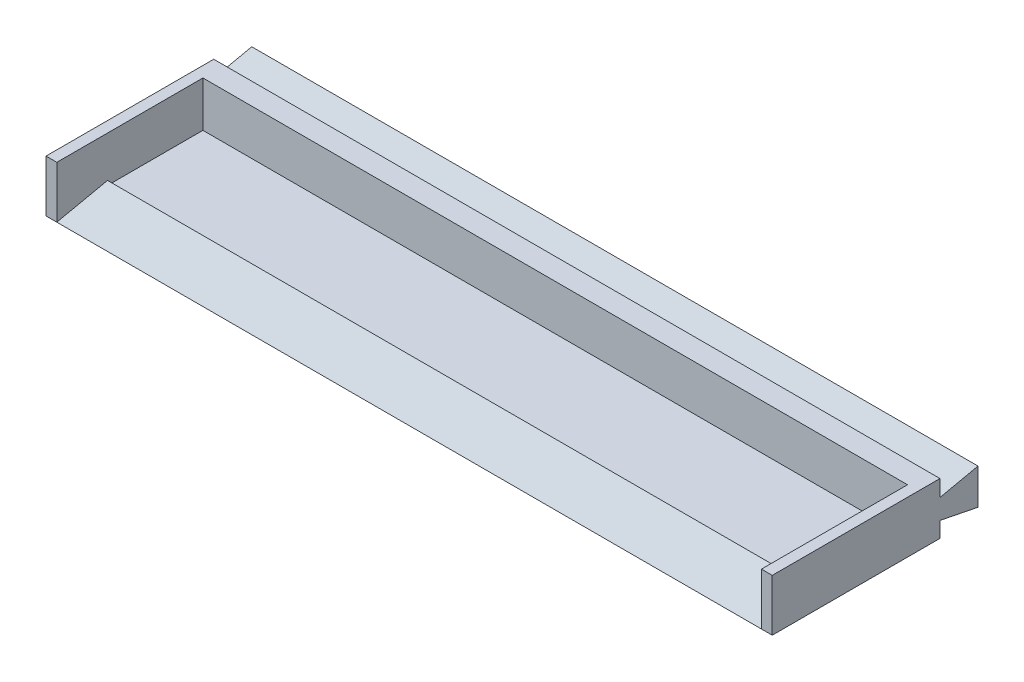
SolidWorks part; units mm, degrees
ref_plane "Front Plane" through (0, 0, 0) normal (0, 0, 1) x (1, 0, 0)
ref_plane "Top Plane" through (0, 0, 0) normal (0, 1, 0) x (1, 0, 0)
ref_plane "Right Plane" through (0, 0, 0) normal (1, 0, 0) x (0, 0, -1)
sketch "Sketch1" plane through (0, 0, 0) normal (0, 1, 0) x (1, 0, 0)
  line L1 (0, 0) -> (163, 0)
  line L2 (0, 0) -> (0, 38.8)
  line L3 (0, 38.8) -> (163, 38.8)
  line L4 (163, 0) -> (163, 38.8)
  dimension "D1" = 38.8
  dimension "D2" = 163
extrude "Boss-Extrude1" add sketch "Sketch1" along normal blind 2.5
sketch "Sketch3" plane through (163, 0, 0) normal (1, 0, 0) x (0, 0, -1)
  line L0 (0, 0) -> (11.7367, 2.5)
  line L1 (0, 2.5) -> (38.8, 2.5) construction
  line L2 (0, 2.5) -> (11.7367, 2.5)
  line L3 (0, 2.5) -> (0, 0)
  dimension "D1" = 12
extrude "Cut-Extrude1" cut sketch "Sketch3" against normal blind 168
sketch "Sketch4" plane through (163, 0, 0) normal (1, 0, 0) x (0, 0, -1)
  line L0 (38.8, 2.5) -> (38.8, 0) construction
  line L1 (11.7367, 2.5) -> (38.8, 2.5)
  line L2 (11.7367, 2.5) -> (11.7367, 1.5)
  line L3 (11.7367, 1.5) -> (38.8, 1.5)
  line L4 (38.8, 2.5) -> (38.8, 1.5)
  dimension "D1" = 1
extrude "Cut-Extrude2" cut sketch "Sketch4" against normal blind 168
sketch "Sketch5" plane through (0, 1.5, 0) normal (0, 1, 0) x (1, 0, 0)
  line L1 (0, 38.8) -> (163, 38.8)
  line L2 (0, 38.8) -> (0, 33.8)
  line L3 (0, 33.8) -> (163, 33.8)
  line L4 (163, 38.8) -> (163, 33.8)
  line L5 (163, 11.7367) -> (163, 38.8) construction
  dimension "D1" = 5
  dimension "D2" = 163
extrude "Boss-Extrude2" add sketch "Sketch5" along normal blind 10.5
sketch "Sketch6" plane through (0, 0, 0) normal (-1, 0, 0) x (0, 0, 1)
  line L1 (-38.8, 12) -> (0, 12)
  line L2 (-38.8, 12) -> (-38.8, 0)
  line L3 (-38.8, 0) -> (0, 0)
  line L4 (0, 12) -> (0, 0)
extrude "Boss-Extrude3" add sketch "Sketch6" along normal blind 2.5
sketch "Sketch7" plane through (163, 0, 0) normal (1, 0, 0) x (0, 0, -1)
  line L1 (0, 0) -> (38.8, 0)
  line L2 (0, 0) -> (0, 12)
  line L3 (0, 12) -> (38.8, 12)
  line L4 (38.8, 0) -> (38.8, 12)
extrude "Boss-Extrude4" add sketch "Sketch7" along normal blind 2.5
sketch "Sketch8" plane through (0, 0, -38.8) normal (0, 0, -1) x (-1, 0, 0)
  line L0 (2.5, 12) -> (2.5, 0) construction
  line L1 (-165.5, 12) -> (2.5, 12)
  line L2 (-165.5, 12) -> (-165.5, 0)
  line L3 (-165.5, 0) -> (2.5, 0)
  line L4 (2.5, 12) -> (2.5, 0)
  dimension "D1" = 12
extrude "Boss-Extrude5" add sketch "Sketch8" along normal blind 8.8
sketch "Sketch9" plane through (165.5, 0, 0) normal (1, 0, 0) x (0, 0, -1)
  line L1 (38.8, 12) -> (38.8, 8.2)
  line L2 (47.6, 12) -> (0, 12) construction
  line L8 (38.8, 8.2) -> (38.8, 3.6)
  line L10 (47.8, 0) -> (38.8, 0)
  line L12 (38.8, 12) -> (47.6, 12)
  line L15 (38.8, 10.1) -> (47.6, 10.1)
  line L16 (47.6, 10.1) -> (38.8, 8.2)
  line L17 (38.8, 3.6) -> (47.8, 1.8)
  line L18 (47.6, 10.1) -> (47.6, 12)
  line L19 (38.8, 12) -> (47.6, 12)
  line L20 (47.6, 12) -> (47.6, 10.1)
  line L21 (47.8, 1.8) -> (47.8, 0)
  line L22 (38.8, 0) -> (47.8, 0)
  line L23 (38.8, 1.8) -> (38.8, 3.6)
  line L24 (47.6, 12) -> (47.6, 0) construction
  line L25 (38.8, 1.8) -> (47.8, 1.8)
  line L26 (38.8, 1.8) -> (38.8, 0)
  line L27 (38.8, 10.1) -> (38.8, 8.2)
  dimension "D1" = 3.6
  dimension "D2" = 3.8
  dimension "D3" = 4.6
extrude "Cut-Extrude3" cut sketch "Sketch9" against normal through all
